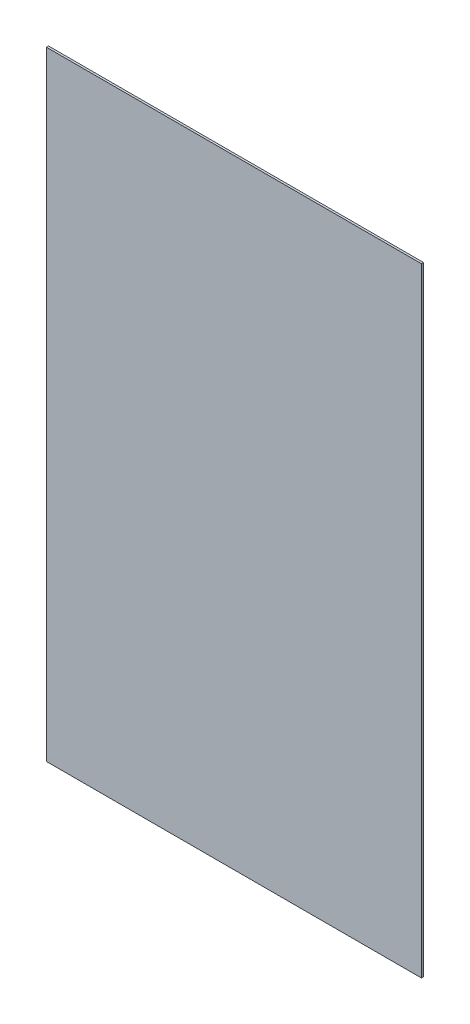
SolidWorks part; units mm, degrees
material "VITON"
ref_plane "Plano frontal" through (0, 0, 0) normal (0, 0, 1) x (1, 0, 0)
ref_plane "Plano superior" through (0, 0, 0) normal (0, 1, 0) x (1, 0, 0)
ref_plane "Plano direito" through (0, 0, 0) normal (1, 0, 0) x (0, 0, -1)
sketch "Esboço1" plane through (0, 0, 0) normal (0, 0, 1) x (1, 0, 0)
  line L1 (-88.5, -146) -> (88.5, -146)
  line L2 (-88.5, -146) -> (-88.5, 146)
  line L3 (-88.5, 146) -> (88.5, 146)
  line L4 (88.5, -146) -> (88.5, 146)
  line L5 (-88.5, -146) -> (88.5, 146) construction
  line L6 (-88.5, 146) -> (88.5, -146) construction
  point P0 (0, 0)
  dimension "D1" = 177
  dimension "D2" = 292
extrude "Ressalto-extrusão1" add sketch "Esboço1" along normal blind 1
